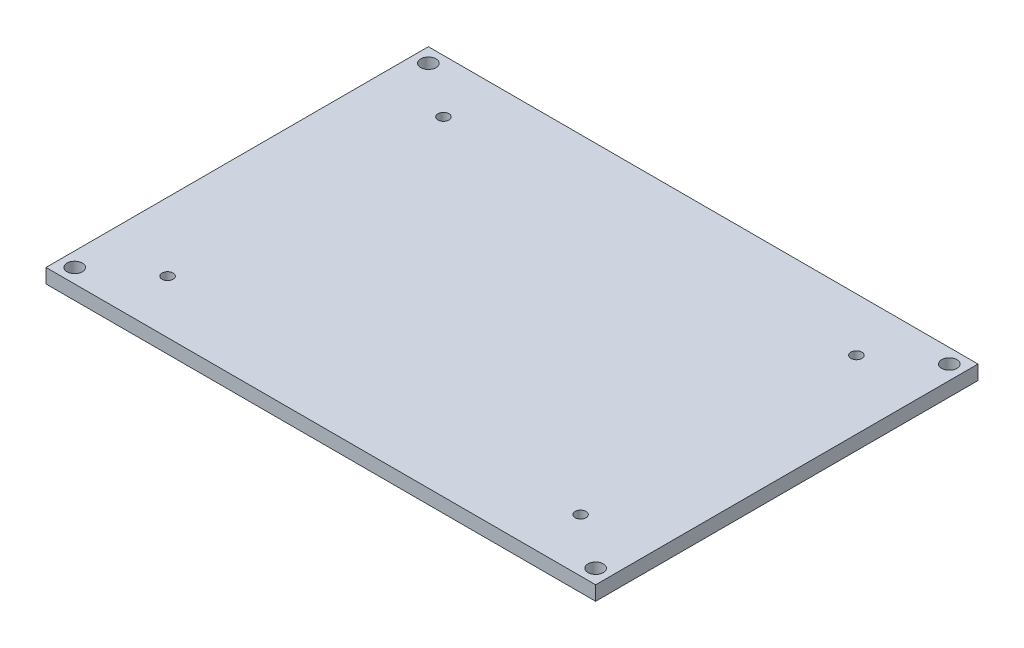
SolidWorks part; units mm, degrees
ref_plane "前视基准面" through (0, 0, 0) normal (0, 0, 1) x (1, 0, 0)
ref_plane "上视基准面" through (0, 0, 0) normal (0, 1, 0) x (1, 0, 0)
ref_plane "右视基准面" through (0, 0, 0) normal (1, 0, 0) x (0, 0, -1)
sketch "草图1" plane through (0, 0, 0) normal (0, 1, 0) x (1, 0, 0)
  line L0 (-43.2, 0) -> (43.2, 0) construction
  line L1 (-57.5, -40) -> (57.5, -40)
  line L2 (-57.5, -40) -> (-57.5, 40)
  line L3 (-57.5, 40) -> (57.5, 40)
  line L4 (57.5, -40) -> (57.5, 40)
  line L5 (-57.5, -40) -> (57.5, 40) construction
  line L6 (-57.5, 40) -> (57.5, -40) construction
  line L7 (-43.2, 28.86) -> (43.2, 28.86) construction
  line L8 (-43.2, 28.86) -> (-43.2, -28.86) construction
  line L9 (-43.2, -28.86) -> (43.2, -28.86) construction
  line L10 (43.2, 28.86) -> (43.2, -28.86) construction
  line L11 (-43.2, 28.86) -> (43.2, -28.86) construction
  line L12 (-43.2, -28.86) -> (43.2, 28.86) construction
  line L13 (0, 28.86) -> (0, -28.86) construction
  circle A0 centre (-43.2, 28.86) radius 1.15
  circle A1 centre (43.2, 28.86) radius 1.15
  circle A2 centre (43.2, -28.86) radius 1.15
  circle A3 centre (-43.2, -28.86) radius 1.15
  circle A4 centre (-54.5, 37) radius 1.6
  circle A5 centre (54.5, 37) radius 1.6
  circle A6 centre (-54.5, -37) radius 1.6
  circle A7 centre (54.5, -37) radius 1.6
  point P0 (0, 0)
  point P6 (0, 0)
  dimension "D5" = 2.3
  dimension "D6" = 3.2
  dimension "D1" = 115
  dimension "D2" = 80
  dimension "D3" = 86.4
  dimension "D4" = 57.72
  dimension "D7" = 3
  dimension "D8" = 3
extrude "凸台-拉伸1" add sketch "草图1" along normal blind 3
